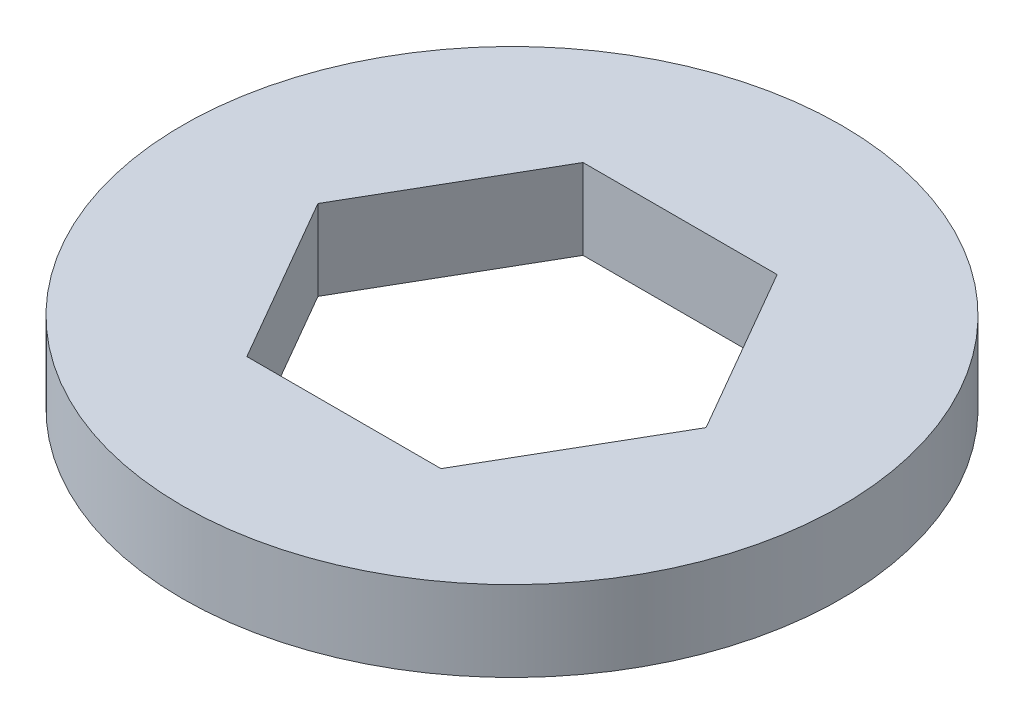
SolidWorks part; units mm, degrees
ref_plane "Front Plane" through (0, 0, 0) normal (0, 0, 1) x (1, 0, 0)
ref_plane "Top Plane" through (0, 0, 0) normal (0, 1, 0) x (1, 0, 0)
ref_plane "Right Plane" through (0, 0, 0) normal (1, 0, 0) x (0, 0, -1)
sketch "Sketch1" plane through (0, 0, 0) normal (0, 1, 0) x (1, 0, 0)
  line L1 (3.7395, 6.477) -> (-3.7395, 6.477)
  line L2 (-3.7395, 6.477) -> (-7.479, 0)
  line L3 (-7.479, 0) -> (-3.7395, -6.477)
  line L4 (-3.7395, -6.477) -> (3.7395, -6.477)
  line L5 (3.7395, -6.477) -> (7.479, 0)
  line L6 (7.479, 0) -> (3.7395, 6.477)
  circle A0 centre (0, 0) radius 12.7
  circle A1 centre (0, 0) radius 6.477 construction
  dimension "D1" = 12.954
  dimension "D2" = 25.4
extrude "Boss-Extrude1" add sketch "Sketch1" along normal blind 3.1 contours A0 L6 L5 L4 L3 L2 L1
